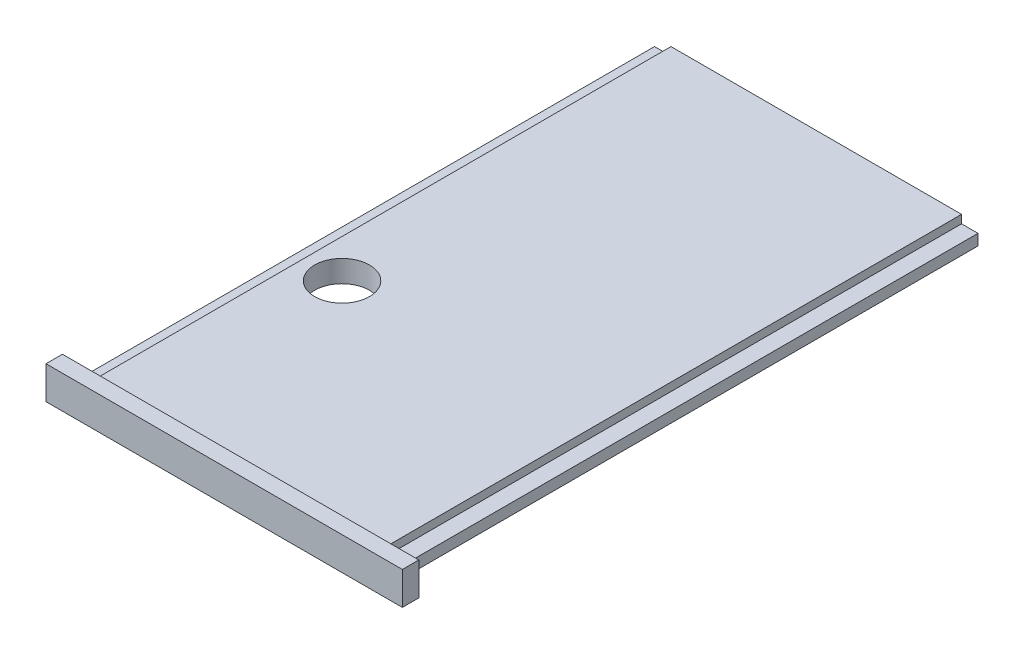
SolidWorks part; units mm, degrees
ref_plane "Front Plane" through (0, 0, 0) normal (0, 0, 1) x (1, 0, 0)
ref_plane "Top Plane" through (0, 0, 0) normal (0, 1, 0) x (1, 0, 0)
ref_plane "Right Plane" through (0, 0, 0) normal (1, 0, 0) x (0, 0, -1)
sketch "Sketch1" plane through (0, 0, 0) normal (0, 0, 1) x (1, 0, 0)
  line L1 (0, 0) -> (65, 0)
  line L2 (0, 0) -> (0, 6)
  line L3 (0, 6) -> (65, 6)
  line L4 (65, 0) -> (65, 6)
  dimension "D1" = 65
  dimension "D2" = 6
extrude "Boss-Extrude1" add sketch "Sketch1" along normal blind 3
sketch "Sketch2" plane through (0, 0, 0) normal (0, 0, -1) x (-1, 0, 0)
  line L1 (-59, 1.1) -> (-6, 1.1)
  line L2 (-59, 1.1) -> (-59, 5.1)
  line L3 (-59, 5.1) -> (-6, 5.1)
  line L4 (-6, 1.1) -> (-6, 5.1)
  line L5 (-65, 0) -> (-65, 6) construction
  line L6 (-59, 3.6) -> (-62, 3.6)
  line L7 (-59, 3.6) -> (-59, 1.6)
  line L8 (-59, 1.6) -> (-62, 1.6)
  line L9 (-62, 3.6) -> (-62, 1.6)
  line L10 (-32.5, 6) -> (-32.5, 15.5393) construction
  line L11 (-65, 6) -> (0, 6) construction
  line L12 (-3, 3.6) -> (-3, 1.6)
  line L13 (-6, 1.6) -> (-3, 1.6)
  line L14 (-6, 3.6) -> (-6, 1.6)
  line L15 (-6, 3.6) -> (-3, 3.6)
  line L17 (0, 0) -> (-65, 0) construction
  dimension "D1" = 2
  dimension "D2" = 3
  dimension "D3" = 4
  dimension "D4" = 3
  dimension "D5" = 0.9
  dimension "D6" = 1.6
extrude "Boss-Extrude2" add sketch "Sketch2" along normal blind 105 contours L3 L4 L1 L2 | L6 L9 L8 L7 | L15 L12 L13 L14
sketch "Sketch3" plane through (0, 5.1, 0) normal (0, 1, 0) x (1, 0, 0)
  line L0 (59, 0) -> (6, 0) construction
  line L1 (6, 105) -> (6, 0) construction
  circle A0 centre (13, 38) radius 5
  dimension "D3" = 10
  dimension "D1" = 38
  dimension "D2" = 7
extrude "Cut-Extrude1" cut sketch "Sketch3" against normal blind 98 contours A0
